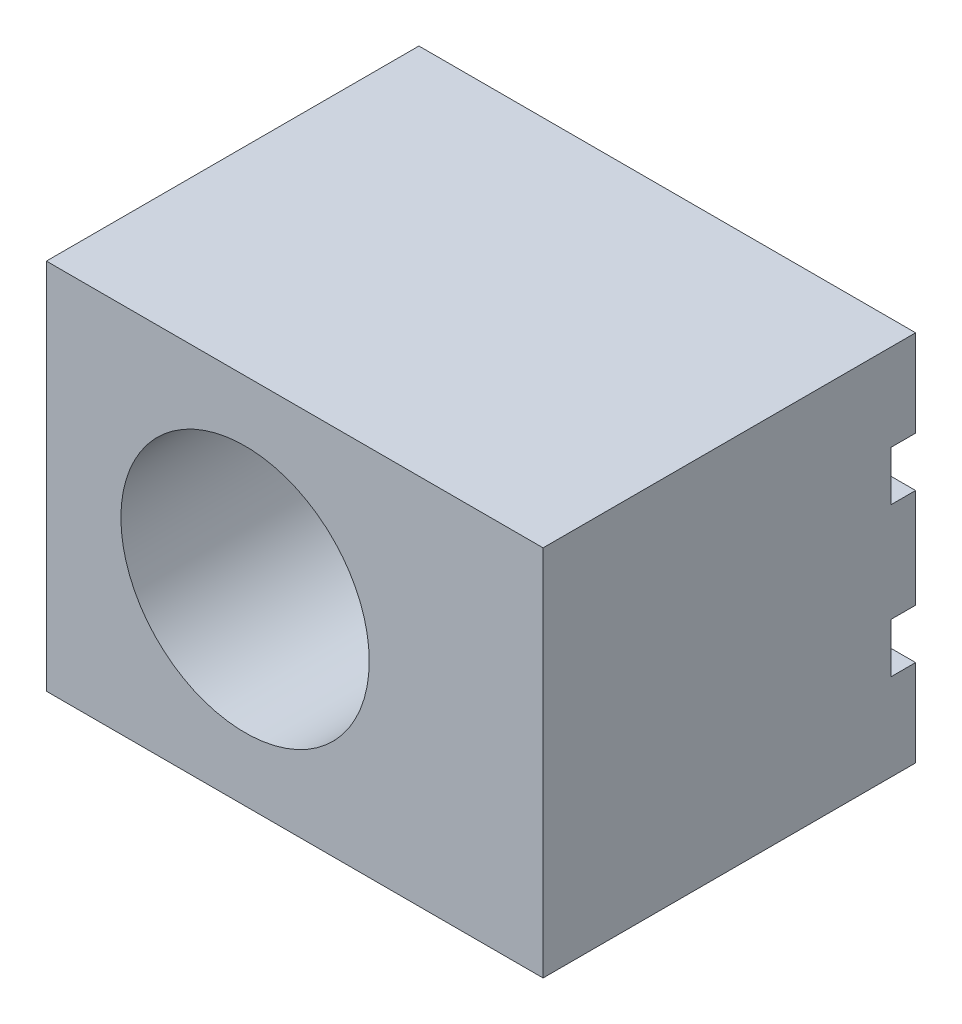
SolidWorks part; units mm, degrees
ref_plane "Front Plane" through (0, 0, 0) normal (1, 0, 0) x (0, 1, 0)
ref_plane "Top Plane" through (0, 0, 0) normal (0, 0, 1) x (0, 1, 0)
ref_plane "Right Plane" through (0, 0, 0) normal (0, 1, 0) x (-1, 0, 0)
sketch "Sketch1" plane through (0, 0, 0) normal (0, 0, 1) x (0, 1, 0)
  line L1 (-3.7766, 4.7074) -> (3.7234, 4.7074)
  line L2 (-3.7766, 4.7074) -> (-3.7766, -5.2926)
  line L3 (-3.7766, -5.2926) -> (3.7234, -5.2926)
  line L4 (3.7234, 4.7074) -> (3.7234, -5.2926)
  dimension "D1" = 7.5
  dimension "D2" = 10
extrude "Boss-Extrude1" add sketch "Sketch1" along normal blind 7.5
sketch "Sketch2" plane through (0, 0, 7.5) normal (0, 0, 1) x (1, 0, 0)
  line L0 (-4.7074, 3.7234) -> (-4.7074, -3.7766) construction
  circle A0 centre (-0.7074, 0) radius 2.5
  dimension "D1" = 5
  dimension "D2" = 4
extrude "Cut-Extrude1" cut sketch "Sketch2" against normal blind 7.5
sketch "Sketch3" plane through (0, 0, 0) normal (0, 0, -1) x (1, 0, 0)
  line L0 (-4.7074, -3.7234) -> (-4.7074, 3.7766) construction
  line L1 (-4.7074, 2.0266) -> (5.2926, 2.0266)
  line L2 (-4.7074, 2.0266) -> (-4.7074, 1.0266)
  line L3 (-4.7074, 1.0266) -> (5.2926, 1.0266)
  line L4 (5.2926, 2.0266) -> (5.2926, 1.0266)
  line L5 (5.2926, 3.7766) -> (5.2926, -3.7234) construction
  line L6 (5.2926, -3.7234) -> (-4.7074, -3.7234) construction
  line L7 (-4.7074, -0.9734) -> (5.2926, -0.9734)
  line L8 (-4.7074, -0.9734) -> (-4.7074, -1.9734)
  line L9 (-4.7074, -1.9734) -> (5.2926, -1.9734)
  line L10 (5.2926, -0.9734) -> (5.2926, -1.9734)
  dimension "D1" = 1
  dimension "D2" = 1
  dimension "D3" = 2
  dimension "D4" = 1.75
extrude "Cut-Extrude2" cut sketch "Sketch3" against normal blind 0.5
